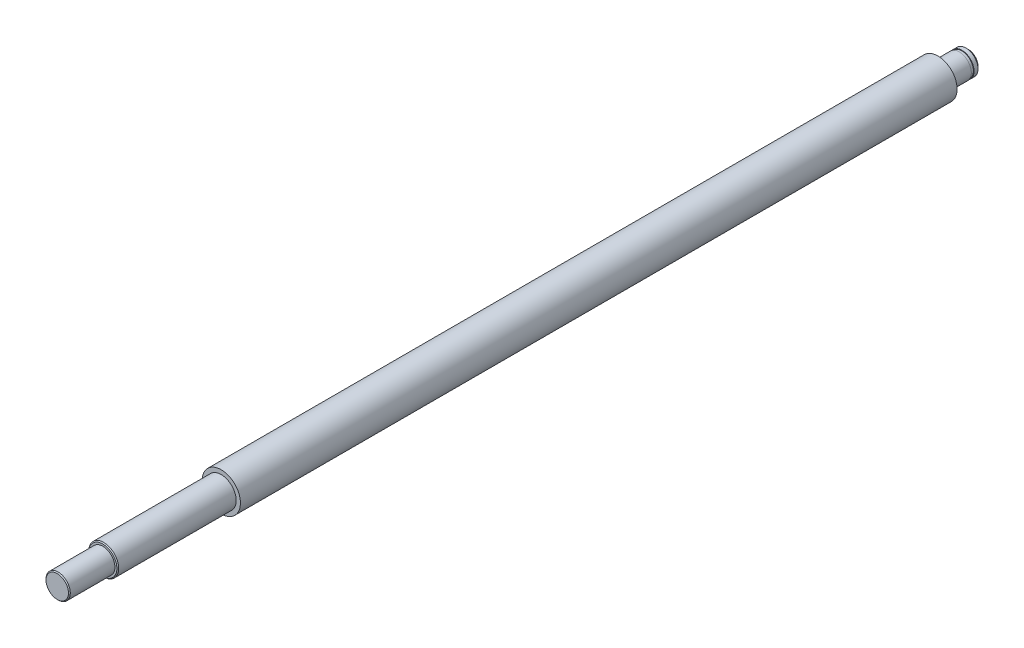
SolidWorks part; units mm, degrees
ref_plane "Front Plane" through (0, 0, 0) normal (0, 0, 1) x (1, 0, 0)
ref_plane "Top Plane" through (0, 0, 0) normal (0, 1, 0) x (1, 0, 0)
ref_plane "Right Plane" through (0, 0, 0) normal (1, 0, 0) x (0, 0, -1)
sketch "Sketch1" plane through (0, 0, 0) normal (1, 0, 0) x (0, 0, -1)
  line L0 (-150, 0) -> (150, 0)
  line L1 (-150, 0) -> (-150, 4)
  line L2 (-150, 4) -> (-135, 4)
  line L3 (-135, 4) -> (-135, 4.94)
  line L4 (-135, 4.94) -> (-96, 4.94)
  line L5 (-96, 4.94) -> (-96, 6.32)
  line L6 (-96, 6.32) -> (140, 6.32)
  line L7 (140, 6.32) -> (140, 4)
  line L8 (140, 4) -> (150, 4)
  line L9 (150, 4) -> (150, 0)
  dimension "D1" = 300
  dimension "D2" = 15
  dimension "D3" = 39
  dimension "D4" = 10
  dimension "D5" = 4
  dimension "D6" = 6.32
  dimension "D7" = 4.94
  dimension "D8" = 4
revolve "Revolve1" add sketch "Sketch1" angle 360 about L0
cosmetic thread "Cosmetic Thread1" [suppressed]
sketch "Sketch2" plane through (0, 0, 0) normal (1, 0, 0) x (0, 0, -1)
  line L0 (150, 4) -> (140, 4) construction
  line L1 (147.9, 4) -> (147, 4)
  line L2 (147.9, 4) -> (147.9, 3.8)
  line L3 (147.9, 3.8) -> (147, 3.8)
  line L4 (147, 4) -> (147, 3.8)
  line L5 (150, -4) -> (150, 4) construction
  line L6 (150, 0) -> (140, 0) construction
  line L7 (140, -6.32) -> (140, 6.32) construction
  dimension "D1" = 0.9
  dimension "D2" = 2.1
  dimension "D3" = 3.8
revolve "Cut-Revolve1" cut sketch "Sketch2" angle 360 about L6
chamfer "Chamfer1" distance 0.8 angle 45 1 edges at (4, 0, -150)
chamfer "Chamfer2" distance 0.3 angle 45 2 edges at (4, 0, 150) (4.94, 0, 135)
equation "\"length\"= 300"
equation "\"D1@Sketch1\" = \"length\""
equation "\"M5_tap\"=4.2mm\t\t\t\t\t\t\t' Below you can do mesurements as follows: cm, mm, ft, in, m, "
equation "\"M5_clearence\"=5.5mm"
equation "\"M6_tap\"=5mm"
equation "\"M6_clearence\"=6.6mm"
equation "\"work_area_width\"=1100mm"
equation "\"work_area_depth\"=900mm"
